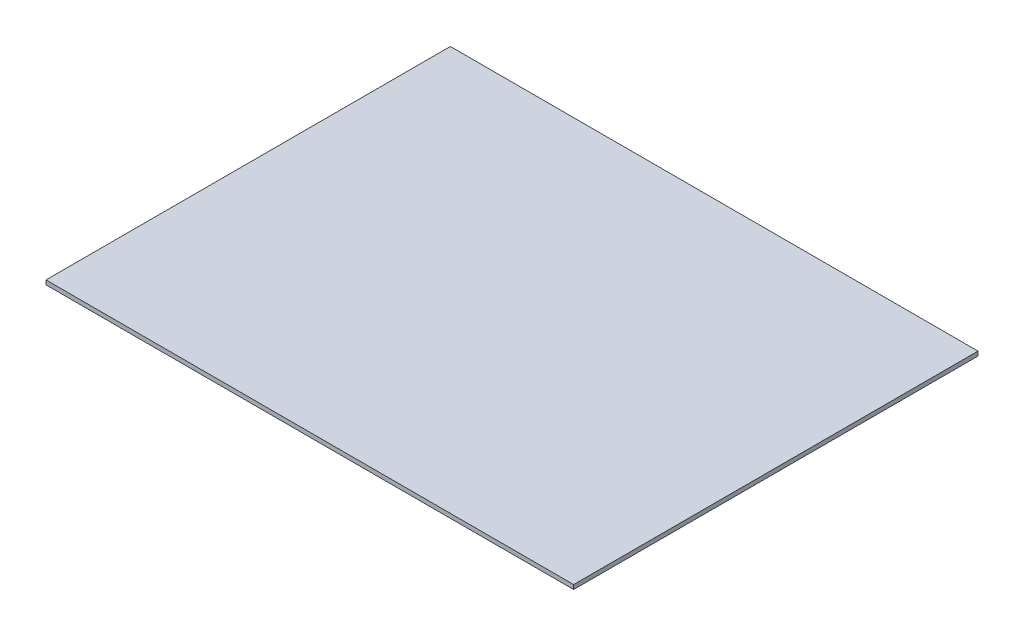
SolidWorks part; units mm, degrees
ref_plane "Front Plane" through (0, 0, 0) normal (0, 0, 1) x (1, 0, 0)
ref_plane "Top Plane" through (0, 0, 0) normal (0, 1, 0) x (1, 0, 0)
ref_plane "Right Plane" through (0, 0, 0) normal (1, 0, 0) x (0, 0, -1)
sketch "Sketch1" plane through (0, 0, 0) normal (0, 1, 0) x (1, 0, 0)
  line L1 (-92, -70.5) -> (92, -70.5)
  line L2 (-92, -70.5) -> (-92, 70.5)
  line L3 (-92, 70.5) -> (92, 70.5)
  line L4 (92, -70.5) -> (92, 70.5)
  line L5 (-92, -70.5) -> (92, 70.5) construction
  line L6 (-92, 70.5) -> (92, -70.5) construction
  point P0 (0, 0)
  dimension "D1" = 184
  dimension "D2" = 141
extrude "Boss-Extrude1" add sketch "Sketch1" along normal blind 1.5
